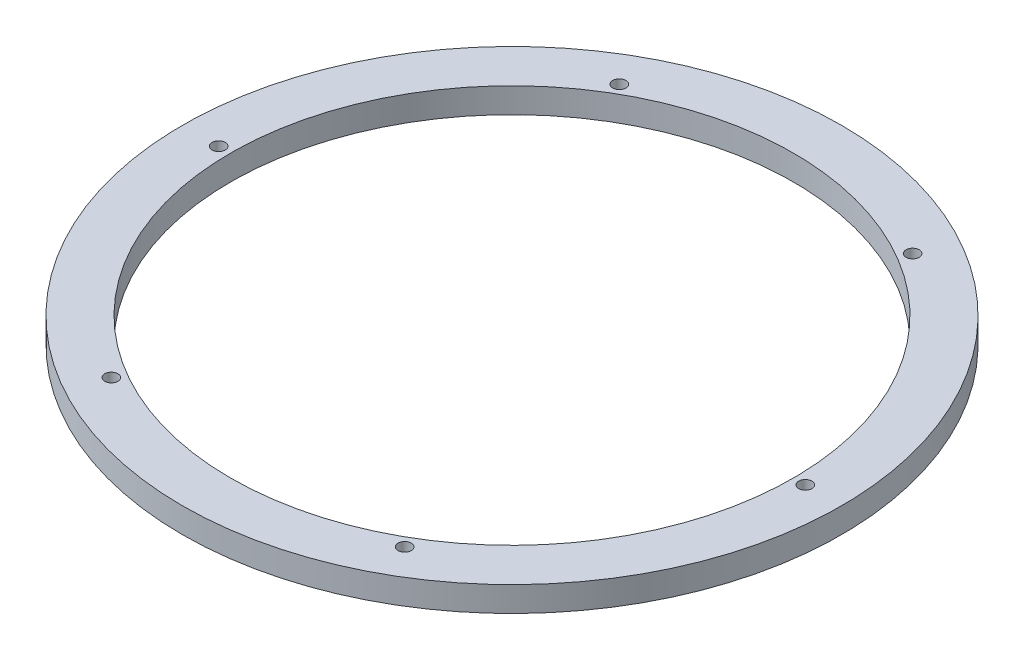
SolidWorks part; units mm, degrees
ref_plane "Front Plane" through (0, 0, 0) normal (0, 0, 1) x (1, 0, 0)
ref_plane "Top Plane" through (0, 0, 0) normal (0, 1, 0) x (1, 0, 0)
ref_plane "Right Plane" through (0, 0, 0) normal (1, 0, 0) x (0, 0, -1)
sketch "Sketch1" plane through (0, 0, 0) normal (0, 1, 0) x (1, 0, 0)
  circle A1 centre (0, 0) radius 250
  circle A3 centre (0, 0) radius 213.5
  dimension "D1" = 500
  dimension "D2" = 427
extrude "Boss-Extrude1" add sketch "Sketch1" along normal mid plane 19
sketch "Sketch2" plane through (0, 9.5, 0) normal (0, 1, 0) x (1, 0, 0)
  line L0 (-1000, 0) -> (49000, 0) construction
  line L1 (0, -1000) -> (0, 49000) construction
  line L2 (-500, 866.0254) -> (24500, -42435.2448) construction
  line L3 (-500, -866.0254) -> (24500, 42435.2448) construction
  circle A0 centre (-111.25, 192.6907) radius 5
  circle A1 centre (-222.5, 0) radius 5
  circle A4 centre (222.5, 0) radius 5
  circle A5 centre (111.25, 192.6907) radius 5
  circle A6 centre (111.25, -192.6907) radius 5
  circle A7 centre (-111.25, -192.6907) radius 5
  dimension "D2" = 10
  dimension "D3" = 10
  dimension "D4" = 222.5
  dimension "D5" = 222.5
  dimension "D1" = 60
extrude "Cut-Extrude1" cut sketch "Sketch2" against normal through all
